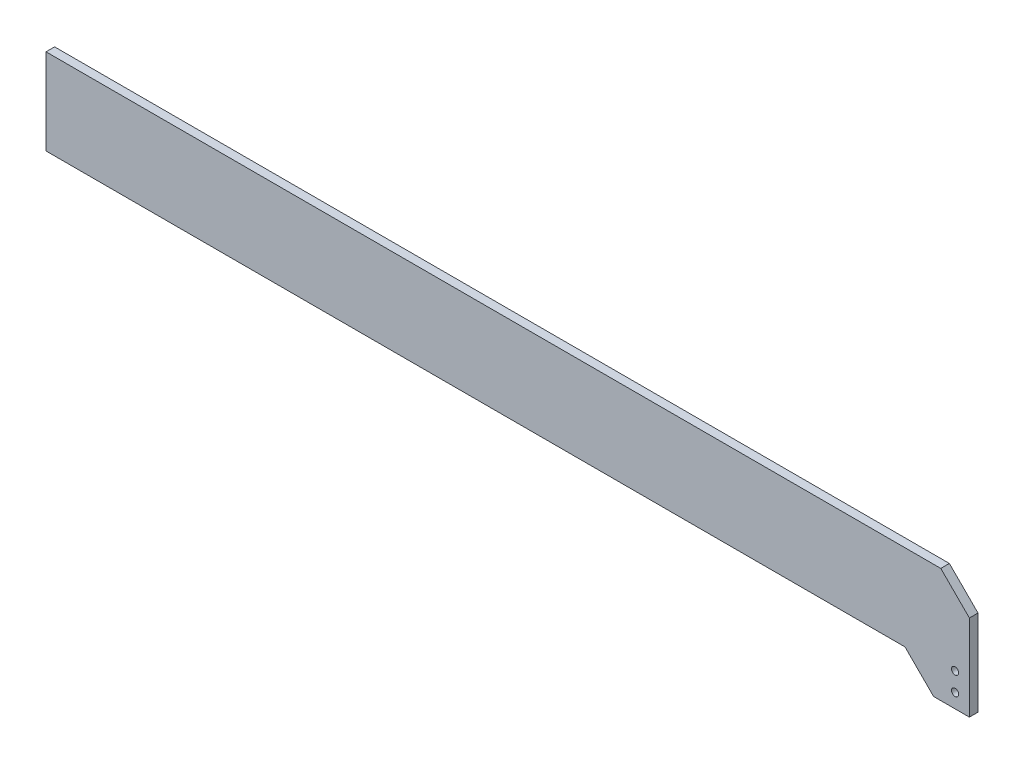
SolidWorks part; units mm, degrees
material "Acrylic (Medium-high impact)"
ref_plane "Front Plane" through (0, 0, 0) normal (0, 0, 1) x (1, 0, 0)
ref_plane "Top Plane" through (0, 0, 0) normal (0, 1, 0) x (1, 0, 0)
ref_plane "Right Plane" through (0, 0, 0) normal (1, 0, 0) x (0, 0, -1)
sketch "Sketch1" plane through (0, 0, 0) normal (0, 0, 1) x (1, 0, 0)
  line L0 (257.6406, 162.7696) -> (277.6406, 142.7696)
  line L1 (-367.3594, 162.7696) -> (257.6406, 162.7696)
  line L2 (-367.3594, 162.7696) -> (-367.3594, 102.7696)
  line L3 (-367.3594, 102.7696) -> (232.6406, 102.7696)
  line L5 (277.6406, 142.7696) -> (277.6406, 82.7696)
  line L6 (277.6406, 82.7696) -> (252.6406, 82.7696)
  line L7 (252.6406, 82.7696) -> (232.6406, 102.7696)
  line L10 (292.0574, 92.7059) -> (252.6406, 82.7696) construction
  circle A0 centre (267.6406, 105.7696) radius 2.5
  circle A1 centre (267.6406, 92.7696) radius 2.5
  point P1 (267.6406, 105.7696)
  point P9 (0, 0)
  dimension "D7" = 5
  dimension "D10" = 5
  dimension "D1" = 60
  dimension "D2" = 600
  dimension "D3" = 45
  dimension "D4" = 10
  dimension "D5" = 360
  dimension "D6" = 20
  dimension "D8" = 20
  dimension "D9" = 3
  dimension "D11" = 10
  dimension "D12" = 0
  dimension "D13" = 15
extrude "Boss-Extrude1" add sketch "Sketch1" along normal blind 6
